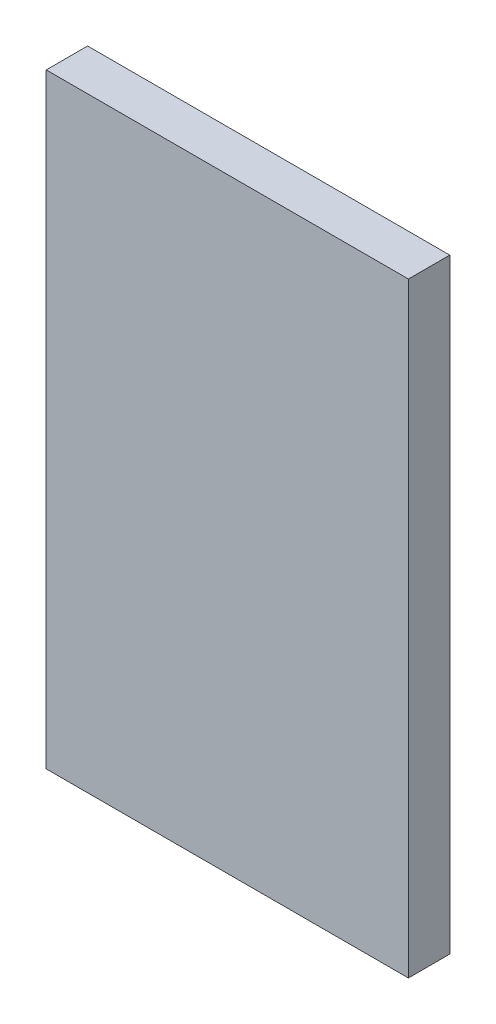
SolidWorks part; units mm, degrees
ref_plane "정면" through (0, 0, 0) normal (0, 0, 1) x (1, 0, 0)
ref_plane "윗면" through (0, 0, 0) normal (0, 1, 0) x (1, 0, 0)
ref_plane "우측면" through (0, 0, 0) normal (1, 0, 0) x (0, 0, -1)
sketch "스케치1" plane through (0, 0, 0) normal (0, 0, 1) x (1, 0, 0)
  line L1 (-39.6843, 39.5752) -> (30.3157, 39.5752)
  line L2 (-39.6843, 39.5752) -> (-39.6843, -77.4248)
  line L3 (-39.6843, -77.4248) -> (30.3157, -77.4248)
  line L4 (30.3157, 39.5752) -> (30.3157, -77.4248)
  dimension "D1" = 70
  dimension "D2" = 117
extrude "보스-돌출1" add sketch "스케치1" along normal blind 8
